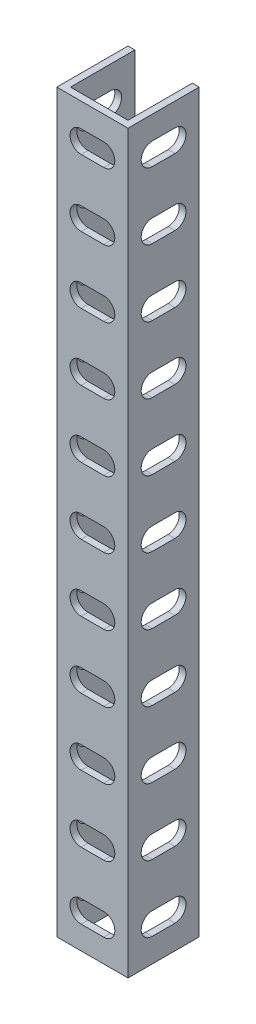
SolidWorks part; units mm, degrees
ref_plane "Front Plane" through (0, 0, 0) normal (0, 0, 1) x (1, 0, 0)
ref_plane "Top Plane" through (0, 0, 0) normal (0, 1, 0) x (1, 0, 0)
ref_plane "Right Plane" through (0, 0, 0) normal (1, 0, 0) x (0, 0, -1)
sketch "Sketch1" plane through (0, 0, 0) normal (0, 0, 1) x (1, 0, 0)
  line L0 (-2.15, 0) -> (2.15, 0) construction
  line L1 (-2.15, 2.11) -> (2.15, 2.11)
  line L2 (-2.15, -2.11) -> (2.15, -2.11)
  line L3 (-2.15, -12.68) -> (2.15, -12.68) construction
  line L4 (-2.15, -10.57) -> (2.15, -10.57)
  line L5 (-2.15, -14.79) -> (2.15, -14.79)
  line L6 (-2.15, -25.36) -> (2.15, -25.36) construction
  line L7 (-2.15, -23.25) -> (2.15, -23.25)
  line L8 (-2.15, -27.47) -> (2.15, -27.47)
  line L9 (-2.15, -38.04) -> (2.15, -38.04) construction
  line L10 (-2.15, -35.93) -> (2.15, -35.93)
  line L11 (-2.15, -40.15) -> (2.15, -40.15)
  line L12 (-2.15, -50.72) -> (2.15, -50.72) construction
  line L13 (-2.15, -48.61) -> (2.15, -48.61)
  line L14 (-2.15, -52.83) -> (2.15, -52.83)
  line L15 (-2.15, -63.4) -> (2.15, -63.4) construction
  line L16 (-2.15, -61.29) -> (2.15, -61.29)
  line L17 (-2.15, -65.51) -> (2.15, -65.51)
  line L18 (-2.15, -76.08) -> (2.15, -76.08) construction
  line L19 (-2.15, -73.97) -> (2.15, -73.97)
  line L20 (-2.15, -78.19) -> (2.15, -78.19)
  line L21 (-2.15, -88.76) -> (2.15, -88.76) construction
  line L22 (-2.15, -86.65) -> (2.15, -86.65)
  line L23 (-2.15, -90.87) -> (2.15, -90.87)
  line L24 (-2.15, -101.44) -> (2.15, -101.44) construction
  line L25 (-2.15, -99.33) -> (2.15, -99.33)
  line L26 (-2.15, -103.55) -> (2.15, -103.55)
  line L27 (-2.15, -114.12) -> (2.15, -114.12) construction
  line L28 (-2.15, -112.01) -> (2.15, -112.01)
  line L29 (-2.15, -116.23) -> (2.15, -116.23)
  line L30 (-2.15, -126.8) -> (2.15, -126.8) construction
  line L31 (-2.15, -124.69) -> (2.15, -124.69)
  line L32 (-2.15, -128.91) -> (2.15, -128.91)
  line L34 (-6.77, 6.67) -> (6.77, 6.67)
  line L35 (-6.77, 6.67) -> (-6.77, -133.33)
  line L36 (-6.77, -133.33) -> (6.77, -133.33)
  line L37 (6.77, 6.67) -> (6.77, -133.33)
  arc A0 (-2.15, 2.11) -> (-2.15, -2.11) centre (-2.15, 0) ccw
  arc A1 (2.15, -2.11) -> (2.15, 2.11) centre (2.15, 0) ccw
  arc A2 (-2.15, -10.57) -> (-2.15, -14.79) centre (-2.15, -12.68) ccw
  arc A3 (2.15, -14.79) -> (2.15, -10.57) centre (2.15, -12.68) ccw
  arc A4 (-2.15, -23.25) -> (-2.15, -27.47) centre (-2.15, -25.36) ccw
  arc A5 (2.15, -27.47) -> (2.15, -23.25) centre (2.15, -25.36) ccw
  arc A6 (-2.15, -35.93) -> (-2.15, -40.15) centre (-2.15, -38.04) ccw
  arc A7 (2.15, -40.15) -> (2.15, -35.93) centre (2.15, -38.04) ccw
  arc A8 (-2.15, -48.61) -> (-2.15, -52.83) centre (-2.15, -50.72) ccw
  arc A9 (2.15, -52.83) -> (2.15, -48.61) centre (2.15, -50.72) ccw
  arc A10 (-2.15, -61.29) -> (-2.15, -65.51) centre (-2.15, -63.4) ccw
  arc A11 (2.15, -65.51) -> (2.15, -61.29) centre (2.15, -63.4) ccw
  arc A12 (-2.15, -73.97) -> (-2.15, -78.19) centre (-2.15, -76.08) ccw
  arc A13 (2.15, -78.19) -> (2.15, -73.97) centre (2.15, -76.08) ccw
  arc A14 (-2.15, -86.65) -> (-2.15, -90.87) centre (-2.15, -88.76) ccw
  arc A15 (2.15, -90.87) -> (2.15, -86.65) centre (2.15, -88.76) ccw
  arc A16 (-2.15, -99.33) -> (-2.15, -103.55) centre (-2.15, -101.44) ccw
  arc A17 (2.15, -103.55) -> (2.15, -99.33) centre (2.15, -101.44) ccw
  arc A18 (-2.15, -112.01) -> (-2.15, -116.23) centre (-2.15, -114.12) ccw
  arc A19 (2.15, -116.23) -> (2.15, -112.01) centre (2.15, -114.12) ccw
  arc A20 (-2.15, -124.69) -> (-2.15, -128.91) centre (-2.15, -126.8) ccw
  arc A21 (2.15, -128.91) -> (2.15, -124.69) centre (2.15, -126.8) ccw
  point P3 (0, 0)
  point P8 (-4.26, 0)
  point P9 (4.26, 0)
  point P12 (0, 0)
  point P13 (0, -12.68)
  point P20 (0, -25.36)
  point P27 (0, -38.04)
  point P34 (0, -50.72)
  point P41 (0, -63.4)
  point P48 (0, -76.08)
  point P55 (0, -88.76)
  point P62 (0, -101.44)
  point P69 (0, -114.12)
  point P76 (0, -126.8)
  point P81 (0, -10.57)
  point P82 (0, 0)
  point P83 (0, 0)
  dimension "D1" = 8.52
  dimension "D2" = 4.22
  dimension "D4" = 8.46
  dimension "D5" = 13.54
  dimension "D6" = 140
  dimension "D7" = 4.42
  dimension "D8" = 2.51
  dimension "D3" = 11
extrude "Boss-Extrude1" add sketch "Sketch1" against normal blind 1.3
sketch "Sketch3" plane through (0, 0, 0) normal (0, 0, 1) x (1, 0, 0)
  line L2 (2.15, 2.11) -> (-2.15, 2.11)
  line L3 (-2.15, -2.11) -> (2.15, -2.11)
  line L4 (2.15, 2.11) -> (-2.15, 2.11)
  line L5 (-2.15, -2.11) -> (2.15, -2.11)
  line L6 (2.15, -35.93) -> (-2.15, -35.93)
  line L7 (-2.15, -40.15) -> (2.15, -40.15)
  line L8 (2.15, -35.93) -> (-2.15, -35.93)
  line L9 (-2.15, -40.15) -> (2.15, -40.15)
  line L10 (2.15, -23.25) -> (-2.15, -23.25)
  line L11 (-2.15, -27.47) -> (2.15, -27.47)
  line L12 (2.15, -23.25) -> (-2.15, -23.25)
  line L13 (-2.15, -27.47) -> (2.15, -27.47)
  line L14 (-2.15, -14.79) -> (2.15, -14.79)
  line L15 (2.15, -10.57) -> (-2.15, -10.57)
  line L16 (-2.15, -14.79) -> (2.15, -14.79)
  line L17 (2.15, -10.57) -> (-2.15, -10.57)
  line L18 (2.15, -61.29) -> (-2.15, -61.29)
  line L19 (-2.15, -65.51) -> (2.15, -65.51)
  line L20 (2.15, -61.29) -> (-2.15, -61.29)
  line L21 (-2.15, -65.51) -> (2.15, -65.51)
  line L22 (2.15, -48.61) -> (-2.15, -48.61)
  line L23 (-2.15, -52.83) -> (2.15, -52.83)
  line L24 (2.15, -48.61) -> (-2.15, -48.61)
  line L25 (-2.15, -52.83) -> (2.15, -52.83)
  line L26 (2.15, -86.65) -> (-2.15, -86.65)
  line L27 (-2.15, -90.87) -> (2.15, -90.87)
  line L28 (2.15, -86.65) -> (-2.15, -86.65)
  line L29 (-2.15, -90.87) -> (2.15, -90.87)
  line L30 (2.15, -73.97) -> (-2.15, -73.97)
  line L31 (-2.15, -78.19) -> (2.15, -78.19)
  line L32 (2.15, -73.97) -> (-2.15, -73.97)
  line L33 (-2.15, -78.19) -> (2.15, -78.19)
  line L34 (2.15, -112.01) -> (-2.15, -112.01)
  line L35 (-2.15, -116.23) -> (2.15, -116.23)
  line L36 (2.15, -112.01) -> (-2.15, -112.01)
  line L37 (-2.15, -116.23) -> (2.15, -116.23)
  line L38 (-2.15, -103.55) -> (2.15, -103.55)
  line L39 (2.15, -99.33) -> (-2.15, -99.33)
  line L40 (-2.15, -103.55) -> (2.15, -103.55)
  line L41 (2.15, -99.33) -> (-2.15, -99.33)
  line L42 (2.15, -124.69) -> (-2.15, -124.69)
  line L43 (-2.15, -128.91) -> (2.15, -128.91)
  line L44 (6.77, 6.67) -> (-6.77, 6.67)
  line L45 (6.77, -133.33) -> (6.77, 6.67)
  line L46 (-6.77, -133.33) -> (6.77, -133.33)
  line L47 (-6.77, 6.67) -> (-6.77, -133.33)
  line L48 (6.77, 6.67) -> (-6.77, 6.67)
  line L49 (6.77, -133.33) -> (6.77, 6.67)
  line L50 (-6.77, -133.33) -> (6.77, -133.33)
  line L51 (-6.77, 6.67) -> (-6.77, -133.33)
  line L52 (2.15, -124.69) -> (-2.15, -124.69)
  line L53 (-2.15, -128.91) -> (2.15, -128.91)
  arc A2 (2.15, -2.11) -> (2.15, 2.11) centre (2.15, 0) ccw
  arc A3 (-2.15, 2.11) -> (-2.15, -2.11) centre (-2.15, 0) ccw
  arc A4 (2.15, -2.11) -> (2.15, 2.11) centre (2.15, 0) ccw
  arc A5 (-2.15, 2.11) -> (-2.15, -2.11) centre (-2.15, 0) ccw
  arc A6 (2.15, -40.15) -> (2.15, -35.93) centre (2.15, -38.04) ccw
  arc A7 (-2.15, -35.93) -> (-2.15, -40.15) centre (-2.15, -38.04) ccw
  arc A8 (2.15, -40.15) -> (2.15, -35.93) centre (2.15, -38.04) ccw
  arc A9 (-2.15, -35.93) -> (-2.15, -40.15) centre (-2.15, -38.04) ccw
  arc A10 (2.15, -27.47) -> (2.15, -23.25) centre (2.15, -25.36) ccw
  arc A11 (-2.15, -23.25) -> (-2.15, -27.47) centre (-2.15, -25.36) ccw
  arc A12 (2.15, -27.47) -> (2.15, -23.25) centre (2.15, -25.36) ccw
  arc A13 (-2.15, -23.25) -> (-2.15, -27.47) centre (-2.15, -25.36) ccw
  arc A14 (2.15, -14.79) -> (2.15, -10.57) centre (2.15, -12.68) ccw
  arc A15 (-2.15, -10.57) -> (-2.15, -14.79) centre (-2.15, -12.68) ccw
  arc A16 (2.15, -14.79) -> (2.15, -10.57) centre (2.15, -12.68) ccw
  arc A17 (-2.15, -10.57) -> (-2.15, -14.79) centre (-2.15, -12.68) ccw
  arc A18 (2.15, -65.51) -> (2.15, -61.29) centre (2.15, -63.4) ccw
  arc A19 (-2.15, -61.29) -> (-2.15, -65.51) centre (-2.15, -63.4) ccw
  arc A20 (2.15, -65.51) -> (2.15, -61.29) centre (2.15, -63.4) ccw
  arc A21 (-2.15, -61.29) -> (-2.15, -65.51) centre (-2.15, -63.4) ccw
  arc A22 (2.15, -52.83) -> (2.15, -48.61) centre (2.15, -50.72) ccw
  arc A23 (-2.15, -48.61) -> (-2.15, -52.83) centre (-2.15, -50.72) ccw
  arc A24 (2.15, -52.83) -> (2.15, -48.61) centre (2.15, -50.72) ccw
  arc A25 (-2.15, -48.61) -> (-2.15, -52.83) centre (-2.15, -50.72) ccw
  arc A26 (2.15, -90.87) -> (2.15, -86.65) centre (2.15, -88.76) ccw
  arc A27 (-2.15, -86.65) -> (-2.15, -90.87) centre (-2.15, -88.76) ccw
  arc A28 (2.15, -90.87) -> (2.15, -86.65) centre (2.15, -88.76) ccw
  arc A29 (-2.15, -86.65) -> (-2.15, -90.87) centre (-2.15, -88.76) ccw
  arc A30 (2.15, -78.19) -> (2.15, -73.97) centre (2.15, -76.08) ccw
  arc A31 (-2.15, -73.97) -> (-2.15, -78.19) centre (-2.15, -76.08) ccw
  arc A32 (2.15, -78.19) -> (2.15, -73.97) centre (2.15, -76.08) ccw
  arc A33 (-2.15, -73.97) -> (-2.15, -78.19) centre (-2.15, -76.08) ccw
  arc A34 (2.15, -116.23) -> (2.15, -112.01) centre (2.15, -114.12) ccw
  arc A35 (-2.15, -112.01) -> (-2.15, -116.23) centre (-2.15, -114.12) ccw
  arc A36 (2.15, -116.23) -> (2.15, -112.01) centre (2.15, -114.12) ccw
  arc A37 (-2.15, -112.01) -> (-2.15, -116.23) centre (-2.15, -114.12) ccw
  arc A38 (2.15, -103.55) -> (2.15, -99.33) centre (2.15, -101.44) ccw
  arc A39 (-2.15, -99.33) -> (-2.15, -103.55) centre (-2.15, -101.44) ccw
  arc A40 (2.15, -103.55) -> (2.15, -99.33) centre (2.15, -101.44) ccw
  arc A41 (-2.15, -99.33) -> (-2.15, -103.55) centre (-2.15, -101.44) ccw
  arc A42 (2.15, -128.91) -> (2.15, -124.69) centre (2.15, -126.8) ccw
  arc A43 (-2.15, -124.69) -> (-2.15, -128.91) centre (-2.15, -126.8) ccw
  arc A44 (2.15, -128.91) -> (2.15, -124.69) centre (2.15, -126.8) ccw
  arc A45 (-2.15, -124.69) -> (-2.15, -128.91) centre (-2.15, -126.8) ccw
  point P64 (0, 0)
  dimension "D1" = 0
  dimension "D2" = 0
  dimension "D3" = 0
  dimension "D4" = 0
  dimension "D5" = 0
  dimension "D6" = 0
  dimension "D7" = 0
  dimension "D8" = 0
  dimension "D9" = 0
  dimension "D10" = 0
  dimension "D11" = 0
  dimension "D12" = 0
sketch "Sketch5" plane through (6.77, 0, 0) normal (1, 0, 0) x (0, 0, -1)
  line L0 (0, 6.67) -> (0, -133.33) construction
  line L1 (0, 6.67) -> (13.54, 6.67)
  line L2 (0, 6.67) -> (0, -133.33)
  line L3 (0, -133.33) -> (13.54, -133.33)
  line L4 (13.54, 6.67) -> (13.54, -133.33)
  line L5 (4.62, 0.14) -> (8.92, 0.14) construction
  line L6 (4.62, 2.25) -> (8.92, 2.25)
  line L7 (4.62, -1.97) -> (8.92, -1.97)
  line L8 (4.62, -12.54) -> (8.92, -12.54) construction
  line L9 (4.62, -10.43) -> (8.92, -10.43)
  line L10 (4.62, -14.65) -> (8.92, -14.65)
  line L11 (4.62, -25.22) -> (8.92, -25.22) construction
  line L12 (4.62, -23.11) -> (8.92, -23.11)
  line L13 (4.62, -27.33) -> (8.92, -27.33)
  line L14 (4.62, -37.9) -> (8.92, -37.9) construction
  line L15 (4.62, -35.79) -> (8.92, -35.79)
  line L16 (4.62, -40.01) -> (8.92, -40.01)
  line L17 (4.62, -50.58) -> (8.92, -50.58) construction
  line L18 (4.62, -48.47) -> (8.92, -48.47)
  line L19 (4.62, -52.69) -> (8.92, -52.69)
  line L20 (4.62, -63.26) -> (8.92, -63.26) construction
  line L21 (4.62, -61.15) -> (8.92, -61.15)
  line L22 (4.62, -65.37) -> (8.92, -65.37)
  line L23 (4.62, -75.94) -> (8.92, -75.94) construction
  line L24 (4.62, -73.83) -> (8.92, -73.83)
  line L25 (4.62, -78.05) -> (8.92, -78.05)
  line L26 (4.62, -88.62) -> (8.92, -88.62) construction
  line L27 (4.62, -86.51) -> (8.92, -86.51)
  line L28 (4.62, -90.73) -> (8.92, -90.73)
  line L29 (4.62, -101.3) -> (8.92, -101.3) construction
  line L30 (4.62, -99.19) -> (8.92, -99.19)
  line L31 (4.62, -103.41) -> (8.92, -103.41)
  line L32 (4.62, -113.98) -> (8.92, -113.98) construction
  line L33 (4.62, -111.87) -> (8.92, -111.87)
  line L34 (4.62, -116.09) -> (8.92, -116.09)
  line L35 (4.62, -126.66) -> (8.92, -126.66) construction
  line L36 (4.62, -124.55) -> (8.92, -124.55)
  line L37 (4.62, -128.77) -> (8.92, -128.77)
  arc A0 (4.62, 2.25) -> (4.62, -1.97) centre (4.62, 0.14) ccw
  arc A1 (8.92, -1.97) -> (8.92, 2.25) centre (8.92, 0.14) ccw
  arc A2 (4.62, -10.43) -> (4.62, -14.65) centre (4.62, -12.54) ccw
  arc A3 (8.92, -14.65) -> (8.92, -10.43) centre (8.92, -12.54) ccw
  arc A4 (4.62, -23.11) -> (4.62, -27.33) centre (4.62, -25.22) ccw
  arc A5 (8.92, -27.33) -> (8.92, -23.11) centre (8.92, -25.22) ccw
  arc A6 (4.62, -35.79) -> (4.62, -40.01) centre (4.62, -37.9) ccw
  arc A7 (8.92, -40.01) -> (8.92, -35.79) centre (8.92, -37.9) ccw
  arc A8 (4.62, -48.47) -> (4.62, -52.69) centre (4.62, -50.58) ccw
  arc A9 (8.92, -52.69) -> (8.92, -48.47) centre (8.92, -50.58) ccw
  arc A10 (4.62, -61.15) -> (4.62, -65.37) centre (4.62, -63.26) ccw
  arc A11 (8.92, -65.37) -> (8.92, -61.15) centre (8.92, -63.26) ccw
  arc A12 (4.62, -73.83) -> (4.62, -78.05) centre (4.62, -75.94) ccw
  arc A13 (8.92, -78.05) -> (8.92, -73.83) centre (8.92, -75.94) ccw
  arc A14 (4.62, -86.51) -> (4.62, -90.73) centre (4.62, -88.62) ccw
  arc A15 (8.92, -90.73) -> (8.92, -86.51) centre (8.92, -88.62) ccw
  arc A16 (4.62, -99.19) -> (4.62, -103.41) centre (4.62, -101.3) ccw
  arc A17 (8.92, -103.41) -> (8.92, -99.19) centre (8.92, -101.3) ccw
  arc A18 (4.62, -111.87) -> (4.62, -116.09) centre (4.62, -113.98) ccw
  arc A19 (8.92, -116.09) -> (8.92, -111.87) centre (8.92, -113.98) ccw
  arc A20 (4.62, -124.55) -> (4.62, -128.77) centre (4.62, -126.66) ccw
  arc A21 (8.92, -128.77) -> (8.92, -124.55) centre (8.92, -126.66) ccw
  point P8 (6.77, 0.14)
  point P13 (11.03, 0.14)
  point P14 (2.51, 0.14)
  point P20 (6.77, -12.54)
  point P27 (6.77, -25.22)
  point P34 (6.77, -37.9)
  point P41 (6.77, -50.58)
  point P48 (6.77, -63.26)
  point P55 (6.77, -75.94)
  point P62 (6.77, -88.62)
  point P69 (6.77, -101.3)
  point P76 (6.77, -113.98)
  point P83 (6.77, -126.66)
  dimension "D1" = 8.52
  dimension "D2" = 4.22
  dimension "D3" = 4.42
  dimension "D5" = 8.46
  dimension "D6" = 2.51
  dimension "D7" = 13.54
  dimension "D4" = 11
extrude "Boss-Extrude2" add sketch "Sketch5" against normal blind 1.3
mirror "Mirror1" about plane through (0, 0, 0) normal (1, 0, 0) of "Boss-Extrude2"
